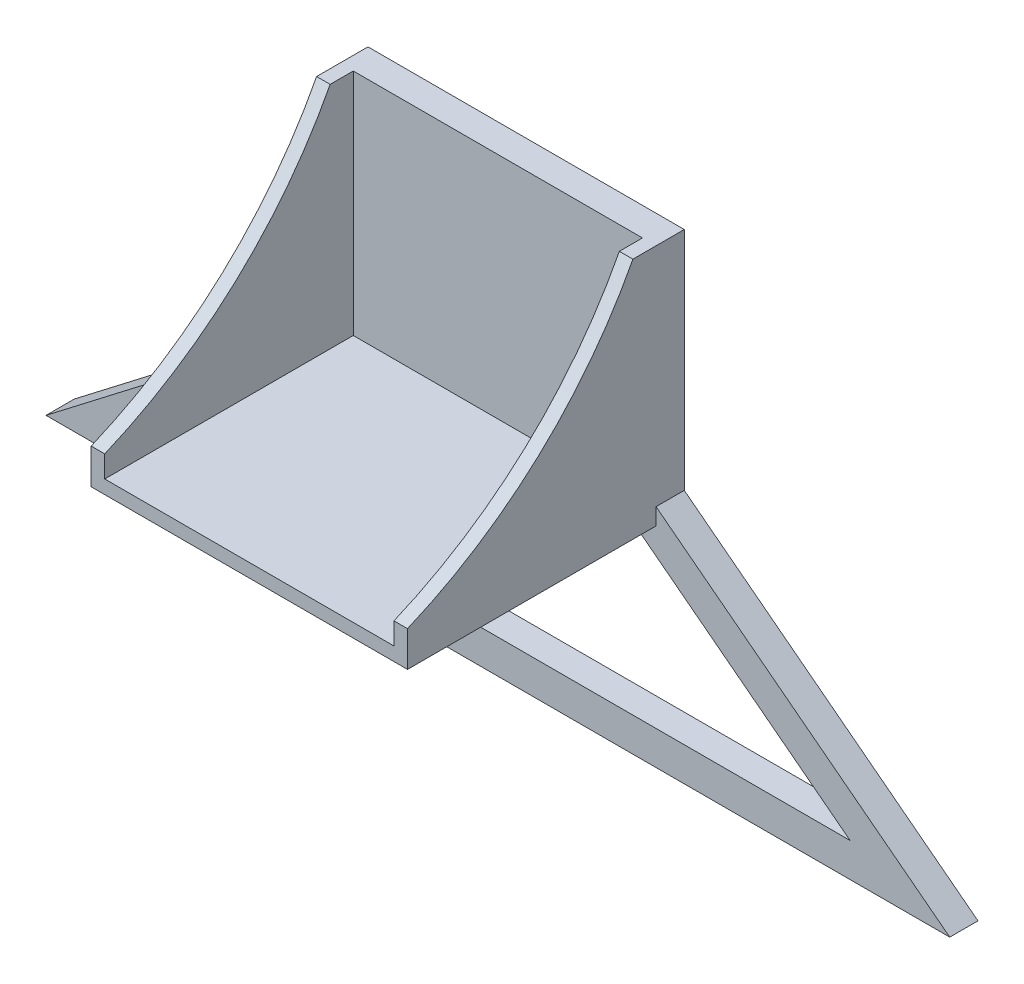
SolidWorks part; units mm, degrees
ref_plane "Front Plane" through (0, 0, 0) normal (0, 0, 1) x (1, 0, 0)
ref_plane "Top Plane" through (0, 0, 0) normal (0, 1, 0) x (1, 0, 0)
ref_plane "Right Plane" through (0, 0, 0) normal (1, 0, 0) x (0, 0, -1)
sketch "Sketch2" plane through (0, 0, 0) normal (0, 0, 1) x (1, 0, 0)
  line L0 (0, 3.7971) -> (0, -40) construction
  line L18 (-14, 0) -> (14, 0)
  line L19 (14, 0) -> (14, -20)
  line L20 (14, -20) -> (40, -40)
  line L21 (40, -40) -> (-40, -40)
  line L22 (-14, -20) -> (-40, -40)
  line L23 (-14, 0) -> (-14, -20)
  line L24 (-11, -21.4772) -> (-31.1796, -37)
  line L25 (31.1796, -37) -> (-31.1796, -37)
  line L26 (11, -21.4772) -> (31.1796, -37)
  line L30 (-11, -21.4772) -> (11, -21.4772)
  line L31 (-11, -3) -> (11, -3) construction
  line L32 (-11, -3) -> (-11, -21.4772) construction
  line L33 (11, -3) -> (11, -21.4772) construction
  point P9 (0, 0)
  dimension "D4" = 40
  dimension "D1" = 40
  dimension "D2" = 14
  dimension "D3" = 20
  dimension "D5" = 3
extrude "Boss-Extrude5" add sketch "Sketch2" along normal blind 2.5 contours L23 L22 L21 L20 L19 L18
sketch "Sketch6" plane through (0, 0, 2.5) normal (0, 0, 1) x (1, 0, 0)
  line L2 (-14, 0) -> (-14, -21.4772)
  line L3 (-14, -21.4772) -> (14, -21.4772)
  line L4 (14, 0) -> (14, -21.4772)
  line L6 (-12.8, 0) -> (-12.8, -20.2772)
  line L7 (-12.8, -20.2772) -> (12.8, -20.2772)
  line L8 (12.8, 0) -> (12.8, -20.2772)
  line L10 (14, -20) -> (14, 0) construction
  line L11 (11, -21.4772) -> (-11, -21.4772) construction
  line L13 (-14, 0) -> (-14, -20) construction
  line L14 (-12.8, 0) -> (-14, 0)
  line L15 (12.8, 0) -> (14, 0)
  line L16 (14, 0) -> (-14, 0) construction
  dimension "D2" = 1.2
  dimension "D3" = 1.2
  dimension "D4" = 1.2
extrude "Boss-Extrude6" add sketch "Sketch6" along normal blind 22
sketch "Sketch7" plane through (-14, 0, 0) normal (-1, 0, 0) x (0, 0, 1)
  line L2 (0, 0) -> (0, -20) construction
  line L3 (24.5, -21.4772) -> (2.5, -21.4772) construction
  circle A0 centre (40, 18.5228) radius 40
  dimension "D3" = 80
  dimension "D1" = 40
  dimension "D2" = 40
extrude "Cut-Extrude2" cut sketch "Sketch7" against normal through all both and the other way through all
